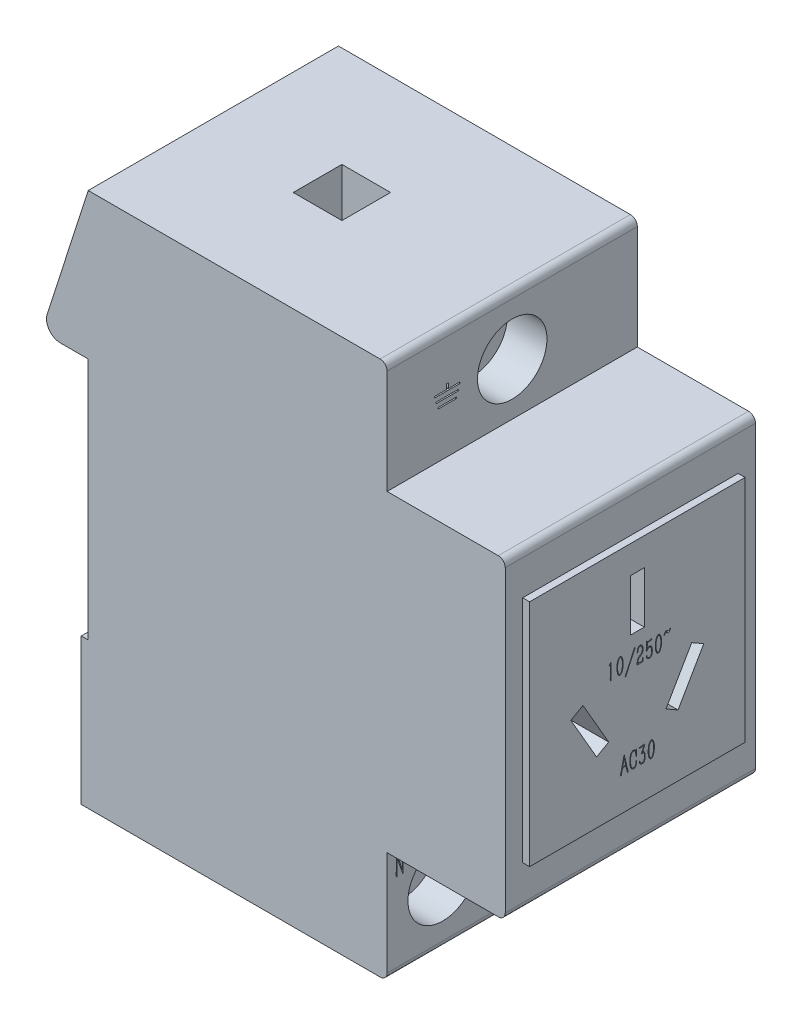
SolidWorks part; units mm, degrees
ref_plane "前视基准面" through (0, 0, 0) normal (0, 0, 1) x (1, 0, 0)
ref_plane "上视基准面" through (0, 0, 0) normal (0, 1, 0) x (1, 0, 0)
ref_plane "右视基准面" through (0, 0, 0) normal (1, 0, 0) x (0, 0, -1)
sketch "主截面" plane through (0, 0, 0) normal (0, 0, 1) x (1, 0, 0)
  line L0 (0, 1) -> (0, 20)
  line L1 (1, 21) -> (5, 21)
  line L2 (5, 21) -> (5, 56)
  line L3 (5, 56) -> (1, 56)
  line L4 (-0.9042, 58.6114) -> (5, 77)
  line L5 (5, 77) -> (47, 77)
  line L6 (48, 76) -> (48, 61)
  line L7 (48, 61) -> (64, 61)
  line L8 (65, 60) -> (65, 17)
  line L9 (64, 16) -> (48, 16)
  line L10 (48, 16) -> (48, 1)
  line L11 (47, 0) -> (1, 0)
  line L12 (65, 38.5) -> (-17.4492, 38.5) construction
  arc A0 (48, 76) -> (47, 77) centre (47, 76) ccw
  arc A1 (65, 60) -> (64, 61) centre (64, 60) ccw
  arc A2 (64, 16) -> (65, 17) centre (64, 17) ccw
  arc A3 (1, 56) -> (-0.9042, 58.6114) centre (1, 58) cw
  arc A4 (47, 0) -> (48, 1) centre (47, 1) ccw
  arc A5 (1, 0) -> (0, 1) centre (1, 1) cw
  arc A6 (1, 21) -> (0, 20) centre (1, 20) ccw
  point P16 (5, 38.5)
  point P23 (48, 77)
  point P26 (65, 61)
  point P29 (65, 16)
  point P34 (48, 0)
  point P37 (0, 0)
  point P40 (0, 21)
  dimension "D7" = 1
  dimension "D8" = 1
  dimension "D9" = 1
  dimension "D10" = 2
  dimension "D11" = 1
  dimension "D12" = 1
  dimension "D13" = 1
  dimension "D1" = 48
  dimension "D2" = 35
  dimension "D3" = 45
  dimension "D4" = 16
  dimension "D5" = 17
  dimension "D6" = 5
extrude "凸台-拉伸1" add sketch "主截面" along normal mid plane 36
sketch "草图2" plane through (5, 0, 0) normal (-1, 0, 0) x (0, 0, 1)
  line L0 (0, -1.6845) -> (0, 66.7707) construction
  line L1 (-18, 38.5) -> (18, 38.5) construction
  line L2 (-18, 56) -> (-18, 21) construction
  line L3 (18, 56) -> (18, 21) construction
  line L5 (16, 22.5001) -> (-16, 22.5001)
  line L6 (16, 22.5001) -> (16, 54.5001)
  line L7 (16, 54.5001) -> (-16, 54.5001)
  line L8 (-16, 22.5001) -> (-16, 54.5001)
  line L9 (16, 22.5001) -> (-16, 54.5001) construction
  line L10 (16, 54.5001) -> (-16, 22.5001) construction
  point P9 (0, 38.5001)
  dimension "D1" = 2
extrude "切除-拉伸1" cut sketch "草图2" against normal blind 34
sketch "草图3" plane through (48, 0, 0) normal (1, 0, 0) x (0, 0, -1)
  line L0 (0, 54.4664) -> (0, 78.831) construction
  line L1 (-18, 68.5) -> (18, 68.5) construction
  line L2 (-18, 61) -> (-18, 76) construction
  line L3 (18, 61) -> (18, 76) construction
hole_wizard "打孔尺寸(%根据)开槽圆柱头螺钉的类型1" positions "草图4" profile "草图5" counterbore size "M5" standard "GB"
sketch "草图4" plane through (48, 0, 0) normal (1, 0, 0) x (0, 0, -1)
  line L0 (-18, 68.5) -> (18, 68.5) construction
  point P0 (0, 68.5)
sketch "草图5" plane through (48, 68.5, 0) normal (0, 1, 0) x (0, 0, -1)
  line L0 (0, 0) -> (0, 9.1524)
  line L1 (0, 9.1524) -> (2.75, 7.5)
  line L2 (2.75, 7.5) -> (2.75, 5.7)
  line L3 (2.75, 5.7) -> (5, 5.7)
  line L4 (5, 5.7) -> (5, 0)
  line L5 (5, 0) -> (0, 0)
  line L10 (0, 9.1524) -> (-2.75, 7.5) construction
  line L11 (0, -6.35) -> (0, 107.95) construction
  dimension "孔直径" = 5.5
  dimension "孔深度" = 7.5
  dimension "柱形沉头孔直径" = 10
  dimension "柱形沉头孔深度" = 5.7
  dimension "导头角度" = 118
sketch "草图6" plane through (48, 0, 0) normal (1, 0, 0) x (0, 0, -1)
  line L0 (0, -2.3244) -> (0, 19.1204) construction
  line L1 (-18, 8.5) -> (18, 8.398) construction
  line L2 (-18, 1) -> (-18, 16) construction
  line L3 (18, 1) -> (18, 16) construction
  line L4 (10, 12.7282) -> (10, 4.0826) construction
  line L5 (-10, 12.7282) -> (-10, 4.0826) construction
  dimension "D1" = 8
hole_wizard "打孔尺寸(%根据)开槽圆柱头螺钉的类型3" positions "草图11" profile "草图12" counterbore size "M5" standard "GB"
sketch "草图11" plane through (48, 0, 0) normal (1, 0, 0) x (0, 0, -1)
  line L0 (10, 12.7282) -> (10, 4.0826) construction
  line L1 (-18, 8.5) -> (18, 8.398) construction
  point P0 (10, 8.4054)
  point P4 (-10.0035, 8.4773)
sketch "草图12" plane through (48, 8.4054, -10) normal (0, 1, 0) x (0, 0, -1)
  line L0 (0, 0) -> (0, 9.1524)
  line L1 (0, 9.1524) -> (2.75, 7.5)
  line L2 (2.75, 7.5) -> (2.75, 5.7)
  line L3 (2.75, 5.7) -> (5, 5.7)
  line L4 (5, 5.7) -> (5, 0)
  line L5 (5, 0) -> (0, 0)
  line L10 (0, 9.1524) -> (-2.75, 7.5) construction
  line L11 (0, -6.35) -> (0, 107.95) construction
  dimension "孔直径" = 5.5
  dimension "孔深度" = 7.5
  dimension "柱形沉头孔直径" = 10
  dimension "柱形沉头孔深度" = 5.7
  dimension "导头角度" = 118
sketch "草图13" plane through (65, 0, 0) normal (1, 0, 0) x (0, 0, -1)
  line L0 (0, 54.4664) -> (0, 17.3083) construction
  line L1 (0, -2.3244) -> (0, 19.1204) construction
  line L2 (-18, 38.5) -> (18, 38.5) construction
  line L3 (-18, 17) -> (-18, 60) construction
  line L4 (18, 17) -> (18, 60) construction
  line L5 (-18, 60) -> (18, 60) construction
  line L6 (-15.5, 55) -> (15.5, 55)
  line L7 (-15.5, 55) -> (-15.5, 22)
  line L8 (-15.5, 22) -> (15.5, 22)
  line L9 (15.5, 55) -> (15.5, 22)
  line L10 (-15.5, 55) -> (15.5, 22) construction
  line L11 (-15.5, 22) -> (15.5, 55) construction
  point P11 (0, 38.5)
  dimension "D1" = 2.5
  dimension "D2" = 5
extrude "凸台-拉伸2" add sketch "草图13" along normal blind 1
sketch "3P插孔" plane through (66, 0, 0) normal (1, 0, 0) x (0, 0, -1)
  line L0 (0, 56.3164) -> (0, 19.8814) construction
  line L1 (0, 54.4664) -> (0, 78.831) construction
  line L2 (-15.5, 38.5) -> (15.5, 38.5) construction
  line L3 (-15.5, 55) -> (-15.5, 22) construction
  line L4 (15.5, 22) -> (15.5, 55) construction
  line L5 (0, 38.5) -> (-16.773, 28.8161) construction
  line L6 (0, 38.5) -> (16.0259, 29.2474) construction
  line L7 (4.1256, 31.8457) -> (5.8576, 30.8457)
  line L8 (-4.1256, 31.8457) -> (-5.8576, 30.8457)
  line L9 (-4.1256, 31.8457) -> (-7.8256, 38.2543)
  line L10 (-7.8256, 38.2543) -> (-9.5576, 37.2543)
  line L11 (-5.8576, 30.8457) -> (-9.5576, 37.2543)
  line L12 (-4.1256, 31.8457) -> (-9.5576, 37.2543) construction
  line L13 (-7.8256, 38.2543) -> (-5.8576, 30.8457) construction
  line L14 (5.8576, 30.8457) -> (9.5576, 37.2543)
  line L15 (7.8256, 38.2543) -> (9.5576, 37.2543)
  line L16 (4.1256, 31.8457) -> (7.8256, 38.2543)
  line L18 (-1, 43.6) -> (1, 43.6)
  line L19 (-1, 43.6) -> (-1, 51)
  line L20 (-1, 51) -> (1, 51)
  line L21 (1, 43.6) -> (1, 51)
  line L22 (-1, 43.6) -> (1, 51) construction
  line L23 (-1, 51) -> (1, 43.6) construction
  point P17 (-6.8416, 34.55)
  point P24 (0, 47.3)
  dimension "D1" = 120
  dimension "D2" = 120
  dimension "D3" = 7.9
  dimension "D4" = 7.4
  dimension "D5" = 2
  dimension "D6" = 8.8
extrude "切除-拉伸2" cut sketch "3P插孔" against normal blind 12
sketch "草图15" plane through (0, 77, 0) normal (0, 1, 0) x (1, 0, 0)
  line L0 (27, 17.564) -> (27, -11.7203) construction
  line L1 (47, -18) -> (47, 18) construction
  line L2 (1.6728, 0) -> (46.6497, 0) construction
  line L4 (20, 3.5) -> (27, 3.5)
  line L5 (20, 3.5) -> (20, -3.5)
  line L6 (20, -3.5) -> (27, -3.5)
  line L7 (27, 3.5) -> (27, -3.5)
  line L8 (20, 3.5) -> (27, -3.5) construction
  line L9 (20, -3.5) -> (27, 3.5) construction
  point P7 (23.5, 0)
  dimension "D1" = 20
  dimension "D2" = 7
extrude "切除-拉伸3" cut sketch "草图15" against normal blind 12
sketch "草图16" plane through (0, 0, 0) normal (0, -1, 0) x (1, 0, 0)
  line L0 (-1.4132, 0) -> (48.521, 0) construction
  line L1 (28, 18.5489) -> (28, -18.6474) construction
  line L3 (48, 18) -> (48, -18) construction
  line L4 (28, 12.5) -> (28, 5.5)
  line L5 (28, -12.5) -> (21, -12.5)
  line L6 (28, -12.5) -> (28, -5.5)
  line L7 (28, -5.5) -> (21, -5.5)
  line L8 (21, -12.5) -> (21, -5.5)
  line L9 (28, -12.5) -> (21, -5.5) construction
  line L10 (28, -5.5) -> (21, -12.5) construction
  line L11 (28, 12.5) -> (21, 12.5)
  line L12 (21, 12.5) -> (21, 5.5)
  line L13 (28, 5.5) -> (21, 5.5)
  point P7 (24.5, -9)
  dimension "D1" = 20
  dimension "D2" = 7
  dimension "D3" = 11
extrude "切除-拉伸4" cut sketch "草图16" against normal blind 12
sketch "草图17" plane through (0, 0, 0) normal (0, -1, 0) x (1, 0, 0)
  line L0 (-3.8098, 0) -> (13.4587, 0) construction
  line L1 (4, 19.7636) -> (4, -19.9323) construction
  line L2 (-1, 18) -> (-1, -18) construction
  line L3 (1, -18) -> (47, -18) construction
  line L4 (4, -9) -> (-1, -9)
  line L5 (4, -9) -> (4, -19.9323)
  line L6 (4, -19.9323) -> (-1, -19.9323)
  line L7 (-1, -9) -> (-1, -19.9323)
  line L8 (-1, 9) -> (-1, 19.9323)
  line L9 (4, 19.9323) -> (-1, 19.9323)
  line L10 (4, 9) -> (4, 19.9323)
  line L11 (4, 9) -> (-1, 9)
  line L13 (4, 6.9928) -> (-1, 6.9928)
  line L14 (4, 6.9928) -> (4, -6.9928)
  line L15 (4, -6.9928) -> (-1, -6.9928)
  line L16 (-1, 6.9928) -> (-1, -6.9928)
  line L17 (4, 6.9928) -> (-1, -6.9928) construction
  line L18 (4, -6.9928) -> (-1, 6.9928) construction
  point P16 (1.5, 0)
  dimension "D1" = 5
  dimension "D2" = 9
extrude "切除-拉伸5" cut sketch "草图17" against normal up to surface (21 mm away) up to face at (3, 21, 0)
sketch "文字10250" plane through (66, 0, 0) normal (1, 0, 0) x (0, 0, -1)
  text T0 "10/250~" font "汉仪长仿宋体" height 2.5
extrude "切除-拉伸6" cut sketch "文字10250" against normal blind 0.25
sketch "文字AC30" plane through (66, 0, 0) normal (1, 0, 0) x (0, 0, -1)
  text T0 "AC30" font "汉仪长仿宋体" height 2.5
extrude "切除-拉伸7" cut sketch "文字AC30" against normal blind 0.25
sketch "文字NL" plane through (48, 0, 0) normal (1, 0, 0) x (0, 0, -1)
  text T0 "N                    L" font "汉仪长仿宋体" height 3
extrude "切除-拉伸8" cut sketch "文字NL" against normal blind 0.25
sketch "接地符号" plane through (48, 0, 0) normal (1, 0, 0) x (0, 0, -1)
  text T0 "⏚" font "新宋体" height 3.5
extrude "切除-拉伸9" cut sketch "接地符号" against normal blind 0.25
